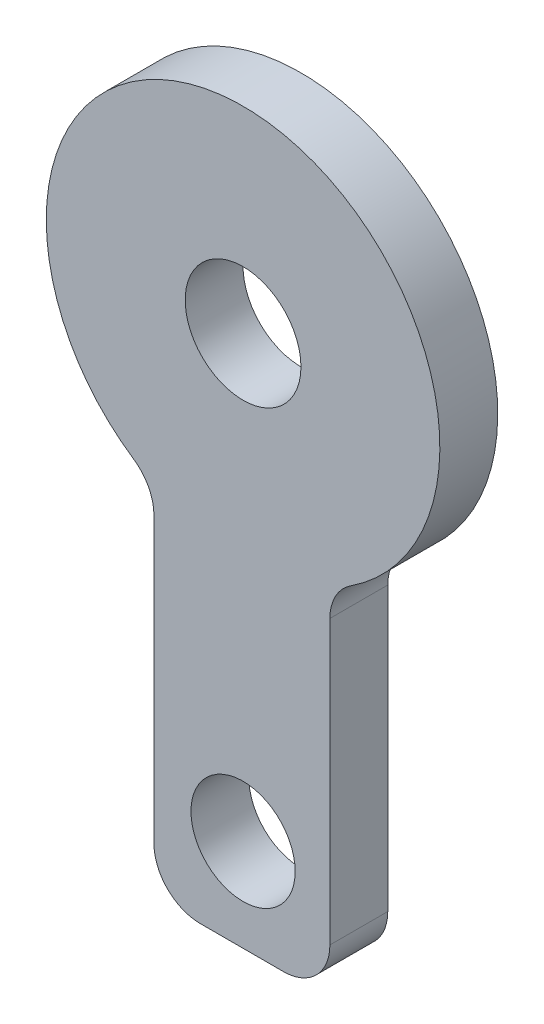
SolidWorks part; units mm, degrees
material "45"
ref_plane "前视基准面" through (0, 0, 0) normal (0, 0, 1) x (1, 0, 0)
ref_plane "上视基准面" through (0, 0, 0) normal (0, 1, 0) x (1, 0, 0)
ref_plane "右视基准面" through (0, 0, 0) normal (1, 0, 0) x (0, 0, -1)
sketch "草图1" plane through (0, 0, 0) normal (0, 0, 1) x (1, 0, 0)
  line L0 (0, 0) -> (0, 11.8555) construction
  line L1 (0, 0) -> (14.1659, -14.1659) construction
  line L2 (0, 0) -> (-9.5379, 9.5379) construction
  line L3 (0, 0) -> (9.2693, 9.2693) construction
  line L4 (0, 0) -> (-10.961, -10.961) construction
  line L5 (0, 0) -> (8.0539, 0) construction
  line L6 (0, 0) -> (0, -21.9632) construction
  line L7 (-3.85, -23) -> (-3.85, -7.5781)
  line L8 (3.75, -23) -> (3.75, -7.6281)
  line L20 (3.75, -23) -> (-3.85, -23)
  arc A0 (3.75, -7.6281) -> (-3.85, -7.5781) centre (0, 0) ccw
  circle A1 centre (0, 0) radius 6 construction
  circle A2 centre (0, 0) radius 2.5
  arc A3 (-3.5355, -3.5355) -> (3.5355, -3.5355) centre (0, 0) ccw construction
  arc A4 (-4.9497, -4.9497) -> (4.9497, -4.9497) centre (0, 0) ccw construction
  arc A5 (3.5355, 3.5355) -> (-3.5355, 3.5355) centre (0, 0) ccw construction
  arc A6 (4.9497, 4.9497) -> (-4.9497, 4.9497) centre (0, 0) ccw construction
  arc A7 (3.5355, 3.5355) -> (4.9497, 4.9497) centre (4.2426, 4.2426) ccw construction
  arc A8 (-3.5355, 3.5355) -> (-4.9497, 4.9497) centre (-4.2426, 4.2426) cw construction
  arc A9 (3.5355, -3.5355) -> (4.9497, -4.9497) centre (4.2426, -4.2426) cw construction
  arc A10 (-3.5355, -3.5355) -> (-4.9497, -4.9497) centre (-4.2426, -4.2426) ccw construction
  circle A11 centre (0, -19) radius 2.25
  dimension "D1" = 17
  dimension "D2" = 7.6
  dimension "D3" = 5
  dimension "D6" = 10
  dimension "D7" = 14
  dimension "D4" = 3.75
  dimension "D12" = 4.5
  dimension "D13" = 4
  dimension "D5" = 23
  dimension "D8" = 90
extrude "拉伸1" add sketch "草图1" along normal blind 2.5
fillet "圆角1" radius 2 4 edges at (-3.85, -23, 1.25) (3.75, -23, 1.25) (3.75, -7.6281, 1.25) (-3.85, -7.5781, 1.25)
